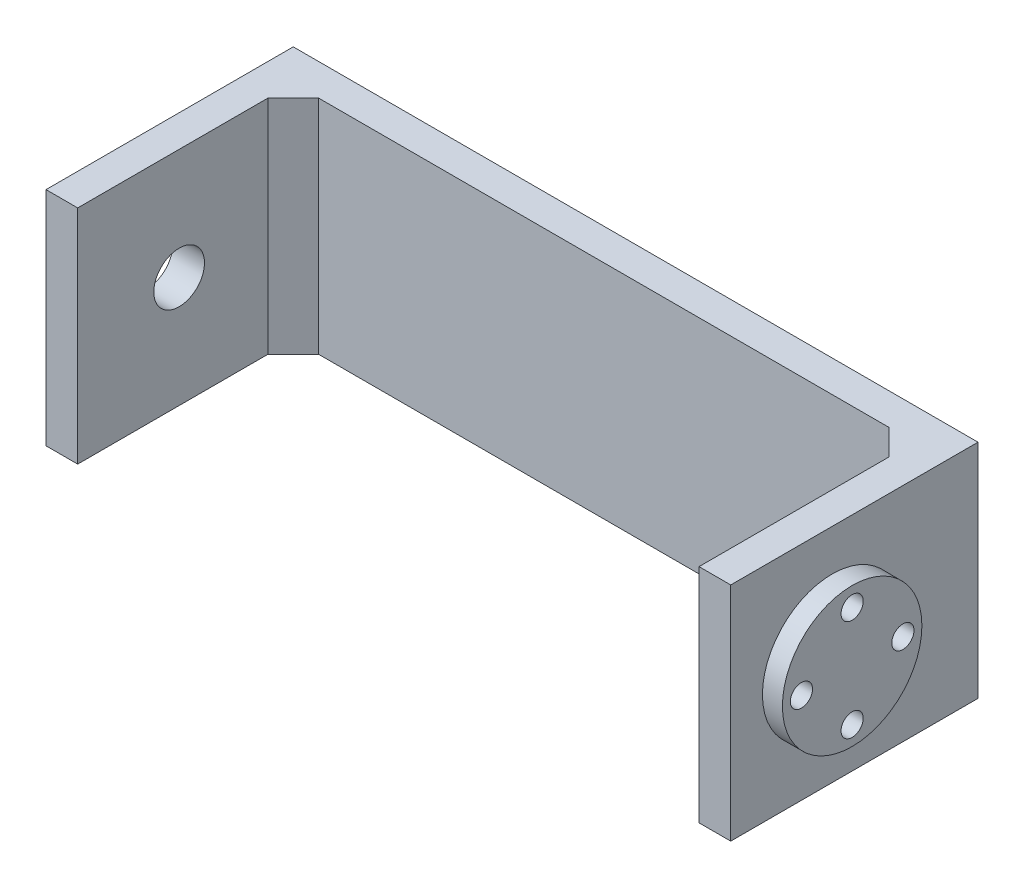
SolidWorks part; units mm, degrees
ref_plane "Front Plane" through (0, 0, 0) normal (0, 0, 1) x (1, 0, 0)
ref_plane "Top Plane" through (0, 0, 0) normal (0, 1, 0) x (1, 0, 0)
ref_plane "Right Plane" through (0, 0, 0) normal (1, 0, 0) x (0, 0, -1)
sketch "Sketch1" plane through (0, 0, 0) normal (0, 1, 0) x (1, 0, 0)
  line L0 (0, 0) -> (0, 39)
  line L1 (0, 39) -> (108, 39)
  line L2 (108, 39) -> (108, 0)
  line L3 (108, 0) -> (103, 0)
  line L4 (103, 0) -> (103, 34)
  line L5 (103, 34) -> (5, 34)
  line L6 (5, 34) -> (5, 0)
  line L7 (5, 0) -> (0, 0)
  dimension "D1" = 98
  dimension "D2" = 5
  dimension "D3" = 5
  dimension "D4" = 39
  dimension "D5" = 34
  dimension "D6" = 39
extrude "Boss-Extrude2" add sketch "Sketch1" along normal blind 35
sketch "Sketch3" plane through (108, 0, 0) normal (1, 0, 0) x (0, 0, -1)
  line L2 (16, 6.5) -> (16, 9.5)
  line L6 (0, 0) -> (39, 0)
  line L7 (39, 0) -> (39, 35)
  line L8 (39, 35) -> (0, 35)
  line L9 (0, 35) -> (0, 0)
  line L10 (0, 0) -> (39, 0)
  line L11 (39, 0) -> (39, 35)
  line L12 (39, 35) -> (0, 35)
  line L13 (0, 35) -> (0, 0)
  circle A0 centre (16, 17.5) radius 11
  circle A1 centre (16, 9.5) radius 1.75
  circle A2 centre (8, 17.5) radius 1.75
  circle A3 centre (16, 25.5) radius 1.75
  circle A4 centre (24, 17.5) radius 1.75
  point P17 (16, 17.5)
  dimension "D2" = 22
  dimension "D4" = 3.5
  dimension "D1" = 0
  dimension "D3" = 3
  dimension "D5" = 4
extrude "Boss-Extrude5" add sketch "Sketch3" along normal blind 3.15
sketch "Sketch5" plane through (108, 0, 0) normal (1, 0, 0) x (0, 0, -1)
  circle A0 centre (16, 9.5) radius 1.75 construction
  circle A1 centre (24, 17.5) radius 1.75 construction
  circle A2 centre (16, 25.5) radius 1.75 construction
  circle A3 centre (8, 17.5) radius 1.75 construction
  circle A4 centre (16, 9.5) radius 1.75
  circle A5 centre (24, 17.5) radius 1.75
  circle A6 centre (16, 25.5) radius 1.75
  circle A7 centre (8, 17.5) radius 1.75
extrude "Cut-Extrude2" cut sketch "Sketch5" against normal up to next
sketch "Sketch6" plane through (103, 0, 0) normal (-1, 0, 0) x (0, 0, 1)
  circle A0 centre (-16, 9.5) radius 2.5
  circle A1 centre (-24, 17.5) radius 2.5
  circle A2 centre (-16, 25.5) radius 2.5
  circle A3 centre (-8, 17.5) radius 2.5
  dimension "D1" = 5
  dimension "D2" = 5
  dimension "D3" = 5
  dimension "D4" = 5
extrude "Cut-Extrude3" cut sketch "Sketch6" against normal blind 2.15
sketch "Sketch7" plane through (0, 0, 0) normal (-1, 0, 0) x (0, 0, 1)
  circle A0 centre (-16, 17.5) radius 4
  dimension "D2" = 8
extrude "Cut-Extrude4" cut sketch "Sketch7" against normal up to next
chamfer "Chamfer1" distance 4 angle 45 2 edges at (5, 17.5, -34) (103, 17.5, -34)
